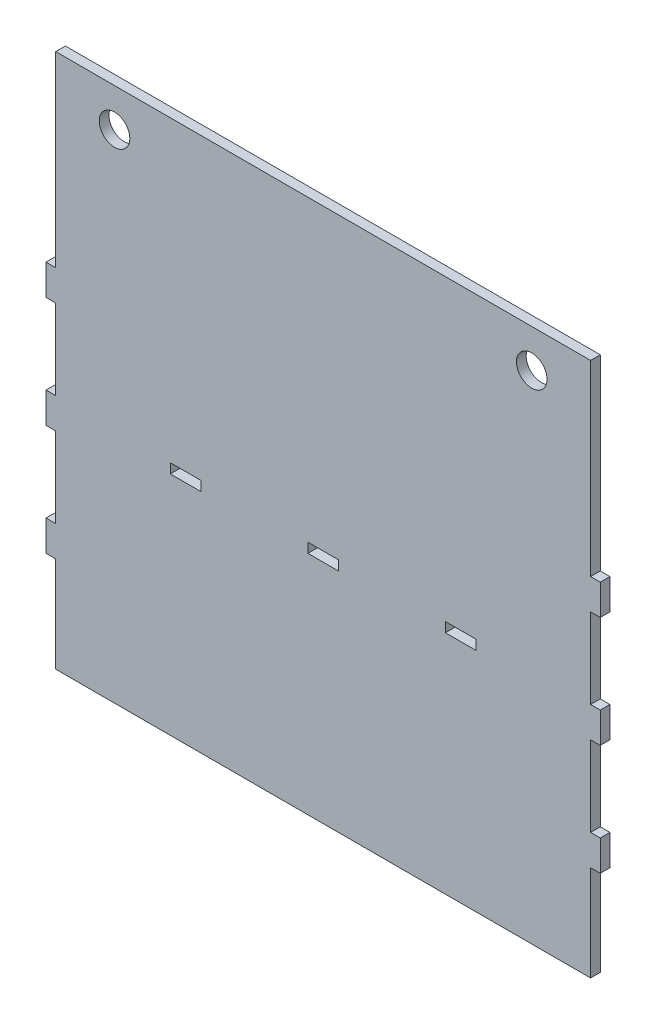
SolidWorks part; units mm, degrees
ref_plane "Alzado" through (0, 0, 0) normal (0, 0, 1) x (1, 0, 0)
ref_plane "Planta" through (0, 0, 0) normal (0, 1, 0) x (1, 0, 0)
ref_plane "Vista lateral" through (0, 0, 0) normal (1, 0, 0) x (0, 0, -1)
sketch "Croquis1" plane through (0, 0, 0) normal (0, 0, 1) x (1, 0, 0)
  line L0 (-175, 175) -> (175, 175)
  line L1 (-175, 175) -> (-175, -175)
  line L2 (-175, -175) -> (175, -175)
  line L3 (175, 175) -> (175, -175)
  point P4 (175, 0)
  point P6 (0, 175)
  dimension "D1" = 350
  dimension "D2" = 350
extrude "Saliente-Extruir1" add sketch "Croquis1" along normal blind 6.35
sketch "Croquis2" plane through (-175, 0, 0) normal (-1, 0, 0) x (0, 0, 1)
  line L0 (0, 175) -> (0, -175) construction
  line L1 (0, 52.5) -> (6.35, 52.5)
  line L2 (0, 52.5) -> (0, 32.5)
  line L3 (0, 32.5) -> (6.35, 32.5)
  line L4 (6.35, 52.5) -> (6.35, 32.5)
  line L5 (6.35, 175) -> (6.35, -175) construction
  line L6 (6.35, -175) -> (0, -175) construction
  line L7 (0, -20) -> (6.35, -20)
  line L8 (0, -20) -> (0, -40)
  line L9 (0, -40) -> (6.35, -40)
  line L10 (6.35, -20) -> (6.35, -40)
  line L11 (0, -92.5) -> (6.35, -92.5)
  line L12 (0, -92.5) -> (0, -112.5)
  line L13 (0, -112.5) -> (6.35, -112.5)
  line L14 (6.35, -92.5) -> (6.35, -112.5)
  dimension "D1" = 62.5
  dimension "D2" = 20
  dimension "D3" = 52.5
  dimension "D4" = 20
  dimension "D5" = 52.5
  dimension "D6" = 20
extrude "Saliente-Extruir2" add sketch "Croquis2" along normal blind 6.35
mirror "Simetría1" about plane through (0, 0, 0) normal (1, 0, 0) of "Saliente-Extruir2"
sketch "Croquis3" plane through (0, 0, 6.35) normal (0, 0, 1) x (1, 0, 0)
  line L1 (-10, -20.49) -> (10, -20.49)
  line L2 (-10, -20.49) -> (-10, -26.84)
  line L3 (-10, -26.84) -> (10, -26.84)
  line L4 (10, -20.49) -> (10, -26.84)
  line L13 (-175, -175) -> (175, -175) construction
  line L14 (80, -20.49) -> (100, -20.49)
  line L15 (80, -20.49) -> (80, -26.84)
  line L16 (80, -26.84) -> (100, -26.84)
  line L17 (100, -20.49) -> (100, -26.84)
  line L18 (-100, -20.49) -> (-80, -20.49)
  line L19 (-100, -20.49) -> (-100, -26.84)
  line L20 (-100, -26.84) -> (-80, -26.84)
  line L21 (-80, -20.49) -> (-80, -26.84)
  point P4 (0, -26.84)
  dimension "D1" = 20
  dimension "D2" = 6.35
  dimension "D3" = 148.16
extrude "Cortar-Extruir1" cut sketch "Croquis3" against normal blind 10
sketch "Croquis4" plane through (0, 0, 6.35) normal (0, 0, 1) x (1, 0, 0)
  line L0 (-136.525, 150) -> (136.525, 150) construction
  line L1 (175, 175) -> (-175, 175) construction
  circle A0 centre (-136.525, 150) radius 10
  circle A1 centre (136.525, 150) radius 10
  point P2 (0, 150)
  dimension "D2" = 20
  dimension "D1" = 25
  dimension "D3" = 273.05
extrude "Cortar-Extruir2" cut sketch "Croquis4" against normal through all
